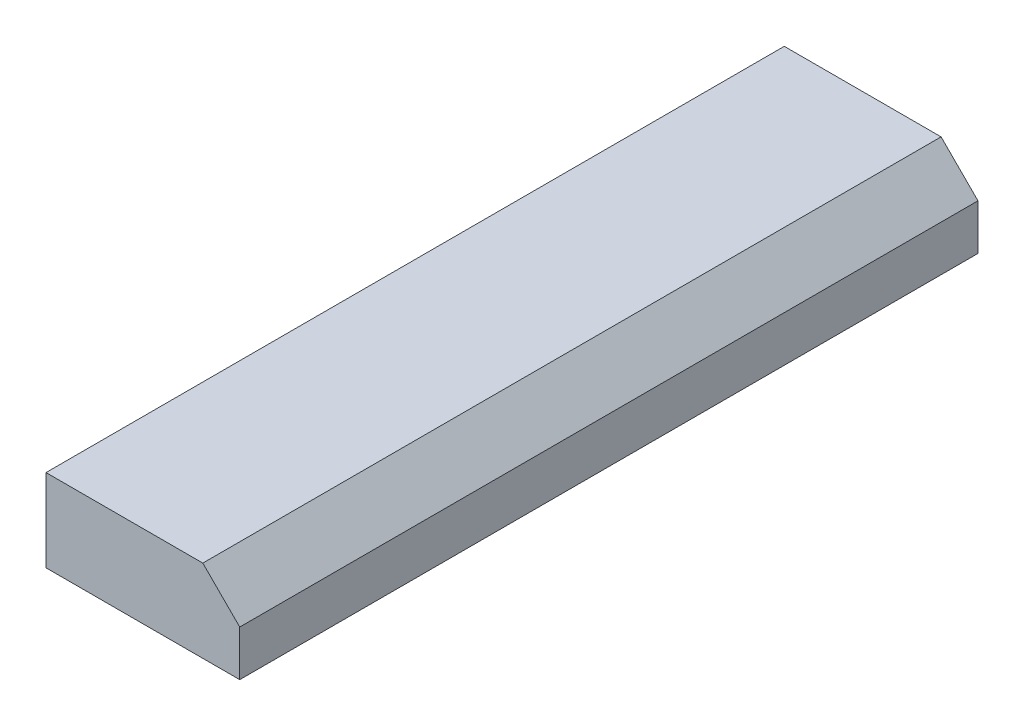
SolidWorks part; units mm, degrees
ref_plane "Ebene vorne" through (0, 0, 0) normal (0, 0, 1) x (1, 0, 0)
ref_plane "Ebene oben" through (0, 0, 0) normal (0, 1, 0) x (1, 0, 0)
ref_plane "Ebene rechts" through (0, 0, 0) normal (1, 0, 0) x (0, 0, -1)
sketch "Skizze1" plane through (0, 0, 0) normal (0, 0, 1) x (1, 0, 0)
  line L0 (-136.0693, 146.6266) -> (-136.0693, 124.273) construction
  line L1 (-188.5516, 124.273) -> (-136.0693, 124.273) construction
  line L2 (-188.5516, 146.6266) -> (-188.5516, 124.273) construction
  line L3 (-188.5516, 146.6266) -> (-136.0693, 146.6266) construction
  line L4 (-136.0693, 146.6266) -> (-136.0693, 124.273)
  line L5 (-188.5516, 124.273) -> (-136.0693, 124.273)
  line L6 (-188.5516, 146.6266) -> (-188.5516, 124.273)
  line L7 (-188.5516, 146.6266) -> (-136.0693, 146.6266)
extrude "Aufsatz-Linear austragen1" add sketch "Skizze1" along normal blind 200
chamfer "Fase1" distance 10 angle 45 1 edges at (-136.0693, 146.6266, 100)
